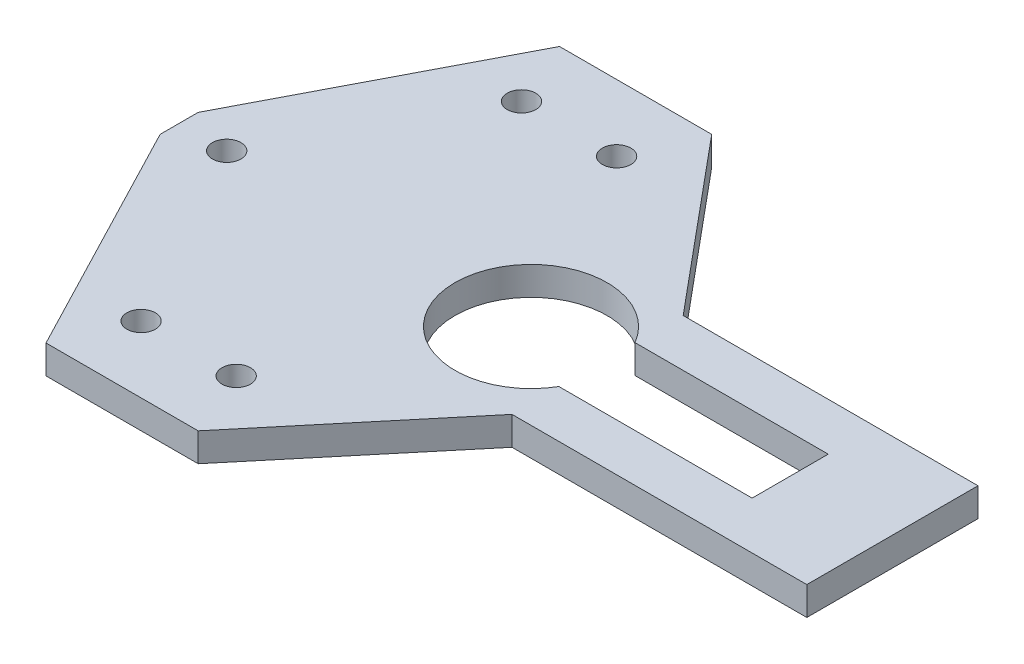
SolidWorks part; units mm, degrees
ref_plane "前视基准面" through (0, 0, 0) normal (0, 0, 1) x (1, 0, 0)
ref_plane "上视基准面" through (0, 0, 0) normal (0, 1, 0) x (1, 0, 0)
ref_plane "右视基准面" through (0, 0, 0) normal (1, 0, 0) x (0, 0, -1)
sketch "草图1" plane through (0, 0, 0) normal (0, 1, 0) x (1, 0, 0)
  line L0 (-703.2833, 0) -> (34460.8796, 0) construction
  line L1 (0, -703.2833) -> (0, 34460.8796) construction
  line L2 (38, -9) -> (38, 9)
  line L3 (38, 9) -> (7, 9)
  line L4 (7, 9) -> (-8, 27)
  line L5 (-8, 27) -> (-24, 27)
  line L6 (-24, 27) -> (-37, 2)
  line L7 (-37, 2) -> (-37, -2)
  line L8 (6.9282, 4) -> (27.25, 4)
  line L9 (27.25, 4) -> (27.25, -4)
  line L10 (6.9282, -4) -> (27.25, -4)
  line L11 (38, -9) -> (7, -9)
  line L12 (7, -9) -> (-8, -27)
  line L13 (-8, -27) -> (-24, -27)
  line L14 (-24, -27) -> (-37, -2)
  arc A0 (6.9282, 4) -> (6.9282, -4) centre (0, 0) ccw
  circle A1 centre (-21, 20) radius 1.5
  circle A2 centre (-11, 20) radius 1.5
  circle A3 centre (-11, -20) radius 1.5
  circle A4 centre (-21, -20) radius 1.5
  circle A5 centre (-32, 0) radius 1.5
  point P22 (38, 0)
  point P23 (27.25, 0)
  point P32 (-37, 0)
  dimension "D1" = 54
  dimension "D9" = 3
  dimension "D11" = 16
  dimension "D16" = 3
  dimension "D2" = 2
  dimension "D3" = 16
  dimension "D4" = 15
  dimension "D5" = 9
  dimension "D6" = 38
  dimension "D7" = 13
  dimension "D8" = 37
  dimension "D10" = 4
  dimension "D12" = 27.25
  dimension "D13" = 10
  dimension "D14" = 11
  dimension "D15" = 40
  dimension "D17" = 32
extrude "凸台-拉伸1" add sketch "草图1" along normal blind 3
